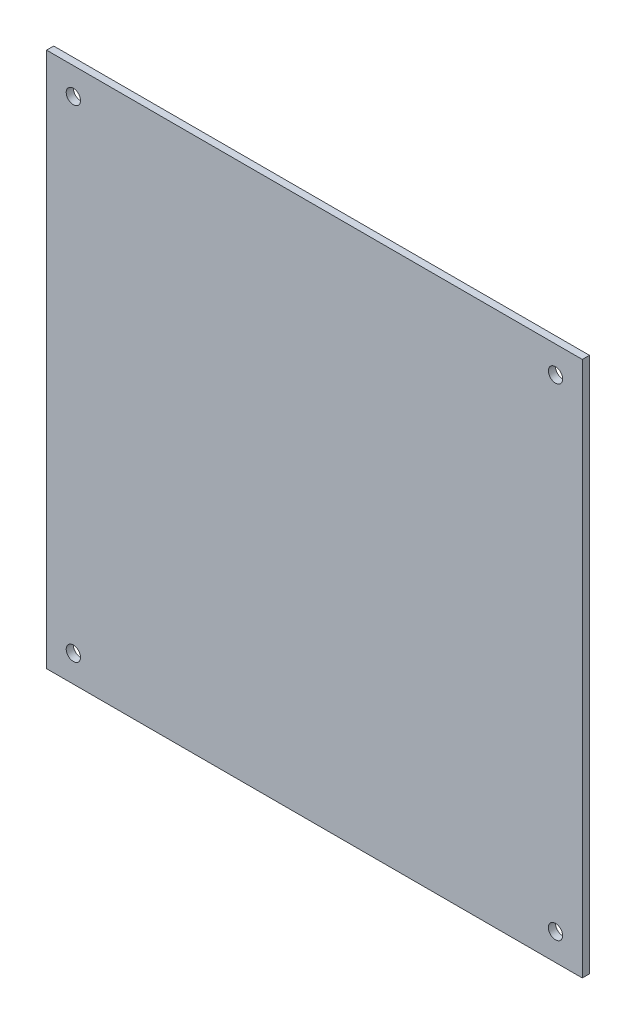
SolidWorks part; units mm, degrees
ref_plane "Alzado" through (0, 0, 0) normal (0, 0, 1) x (1, 0, 0)
ref_plane "Planta" through (0, 0, 0) normal (0, 1, 0) x (1, 0, 0)
ref_plane "Vista lateral" through (0, 0, 0) normal (1, 0, 0) x (0, 0, -1)
sketch "Croquis1" plane through (0, 0, 0) normal (0, 0, 1) x (1, 0, 0)
  line L1 (-75, -75) -> (75, -75)
  line L2 (-75, -75) -> (-75, 75)
  line L3 (-75, 75) -> (75, 75)
  line L4 (75, -75) -> (75, 75)
  line L5 (-75, -75) -> (75, 75) construction
  line L6 (-75, 75) -> (75, -75) construction
  point P0 (0, 0)
extrude "Saliente-Extruir1" add sketch "Croquis1" along normal blind 2
sketch "Croquis3" plane through (0, 0, 2) normal (0, 0, 1) x (1, 0, 0)
  line L1 (-67.5, -67.5) -> (67.5, -67.5)
  line L2 (-67.5, -67.5) -> (-67.5, 67.5)
  line L3 (-67.5, 67.5) -> (67.5, 67.5)
  line L4 (67.5, -67.5) -> (67.5, 67.5)
  line L5 (-67.5, -67.5) -> (67.5, 67.5) construction
  line L6 (-67.5, 67.5) -> (67.5, -67.5) construction
  line L11 (-37.5, -37.5) -> (37.5, 37.5) construction
  line L12 (-37.5, 37.5) -> (37.5, -37.5) construction
  circle A0 centre (-67.5, -67.5) radius 2
  circle A1 centre (67.5, -67.5) radius 2
  circle A2 centre (67.5, 67.5) radius 2
  circle A3 centre (-67.5, 67.5) radius 2
  point P0 (0, 0)
  point P6 (0, 0)
  dimension "D1" = 2
  dimension "D2" = 2
extrude "Cortar-Extruir2" cut sketch "Croquis3" against normal blind 2
